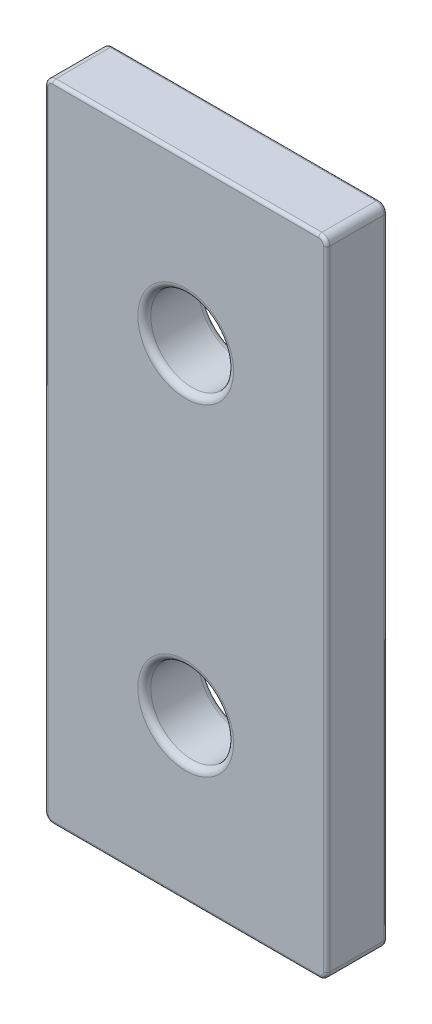
SolidWorks part; units mm, degrees
ref_plane "Front Plane" through (0, 0, 0) normal (0, 0, 1) x (1, 0, 0)
ref_plane "Top Plane" through (0, 0, 0) normal (0, 1, 0) x (1, 0, 0)
ref_plane "Right Plane" through (0, 0, 0) normal (1, 0, 0) x (0, 0, -1)
sketch "Sketch1" plane through (0, 0, 0) normal (0, 0, 1) x (1, 0, 0)
  line L0 (-11.1125, 25.4) -> (-11.1125, -25.4)
  line L1 (-11.1125, 25.4) -> (11.1125, 25.4)
  line L2 (-11.1125, -25.4) -> (11.1125, -25.4)
  line L3 (11.1125, 25.4) -> (11.1125, -25.4)
  line L4 (-11.1125, 0) -> (11.1125, 0) construction
  line L5 (0, -12.7) -> (0, 12.7) construction
  line L6 (-3.175, 12.7) -> (-1.905, 12.7) construction
  circle A0 centre (0, 12.7) radius 3.2639
  circle A2 centre (0, 12.7) radius 3.175 construction
  circle A3 centre (25.4, 12.7) radius 3.2639
  circle A4 centre (25.4, -12.7) radius 3.2639
  circle A5 centre (0, -12.7) radius 3.2639
  dimension "Thru Hole Diameter" = 6.5278
  dimension "Mounting Fastener Thread Size" = 6.35
  dimension "Width" = 22.225
  dimension "Length" = 50.8
  dimension "Mounting Hole Vert CtoC" = 25.4
  dimension "Mounting Fastener Thread Pitch" = 1.27
  dimension "D1" = 12.7
  dimension "D2" = 11.1125
  dimension "Mounting Hole Horiz CtoC" = 25.4
  dimension "Mounting Hole Vertical Offset" = 12.7
  dimension "Mounting Hole Horizontal Offset" = 11.1125
  dimension "D50" = 2
  dimension "Number of Vertical Holes" = 2
sketch "Sketch2" plane through (0, 0, 0) normal (1, 0, 0) x (0, 0, -1)
  line L0 (-2.3876, 12.7) -> (2.3876, 12.7) construction
  line L1 (2.3876, 12.7) -> (10.3124, 12.7) construction
  dimension "Thickness" = 4.7752
  dimension "Mounting Fastener Thread Length" = 12.7
sketch "Sketch3" plane through (0, 0, 0) normal (0, 0, 1) x (1, 0, 0)
  line L0 (-11.1125, 25.4) -> (-11.1125, -25.4) construction
  line L1 (-11.1125, -25.4) -> (11.1125, -25.4) construction
  line L2 (11.1125, 25.4) -> (11.1125, -25.4) construction
  line L3 (-11.1125, 25.4) -> (11.1125, 25.4) construction
  line L4 (-11.1125, 25.4) -> (-11.1125, -25.4)
  line L5 (-11.1125, -25.4) -> (11.1125, -25.4)
  line L6 (11.1125, 25.4) -> (11.1125, -25.4)
  line L7 (-11.1125, 25.4) -> (11.1125, 25.4)
extrude "Boss-Extrude1" add sketch "Sketch3" along normal up to vertex (2.3876 mm away) from vertex at -2.3876 starting at point (0, 12.7, -2.3876)
fillet "Fillet1" radius 0.635 4 edges at (11.1125, -25.4, 0) (-11.1125, -25.4, 0) (-11.1125, 25.4, 0) (11.1125, 25.4, 0)
sketch "Sketch4" plane through (0, 0, 2.3876) normal (0, 0, 1) x (1, 0, 0)
  circle A0 centre (0, 12.7) radius 3.2639 construction
  circle A1 centre (0, 12.7) radius 3.2639
extrude "Cut-Extrude1" cut sketch "Sketch4" against normal through all
pattern_linear "LPattern1" count 2 spacing 25.4 along (0, -1, 0) count 2 spacing 25.4 along (-1, 0, 0) of "Cut-Extrude1"
fillet "Fillet2" radius 0.254 16 edges at (10.9265, -25.214, -2.3876) (0, -25.4, -2.3876) (-10.9265, -25.214, -2.3876) (-11.1125, 0, -2.3876) (-10.9265, 25.214, -2.3876) (0, 25.4, -2.3876) (10.9265, 25.214, -2.3876) (10.9265, -25.214, 2.3876) (0, -25.4, 2.3876) (-10.9265, -25.214, 2.3876) (-11.1125, 0, 2.3876) (-10.9265, 25.214, 2.3876) (0, 25.4, 2.3876) (10.9265, 25.214, 2.3876) (11.1125, 0, -2.3876) (11.1125, 0, 2.3876)
fillet "Fillet3" radius 0.508 4 edges at (3.2639, 12.7, -2.3876) (3.2639, -12.7, -2.3876) (3.2639, 12.7, 2.3876) (3.2639, -12.7, 2.3876)
equation "\"D1@LPattern1\"=\"Number of Vertical Holes@Sketch1\""
equation "\"D4@LPattern1\"=\"D3@LPattern1\""
equation "\"D3@LPattern1\"=\"Mounting Hole Vert CtoC@Sketch1\""
equation "\"Mounting Hole Horiz CtoC@Sketch1\"=\"Mounting Hole Vert CtoC@Sketch1\""
